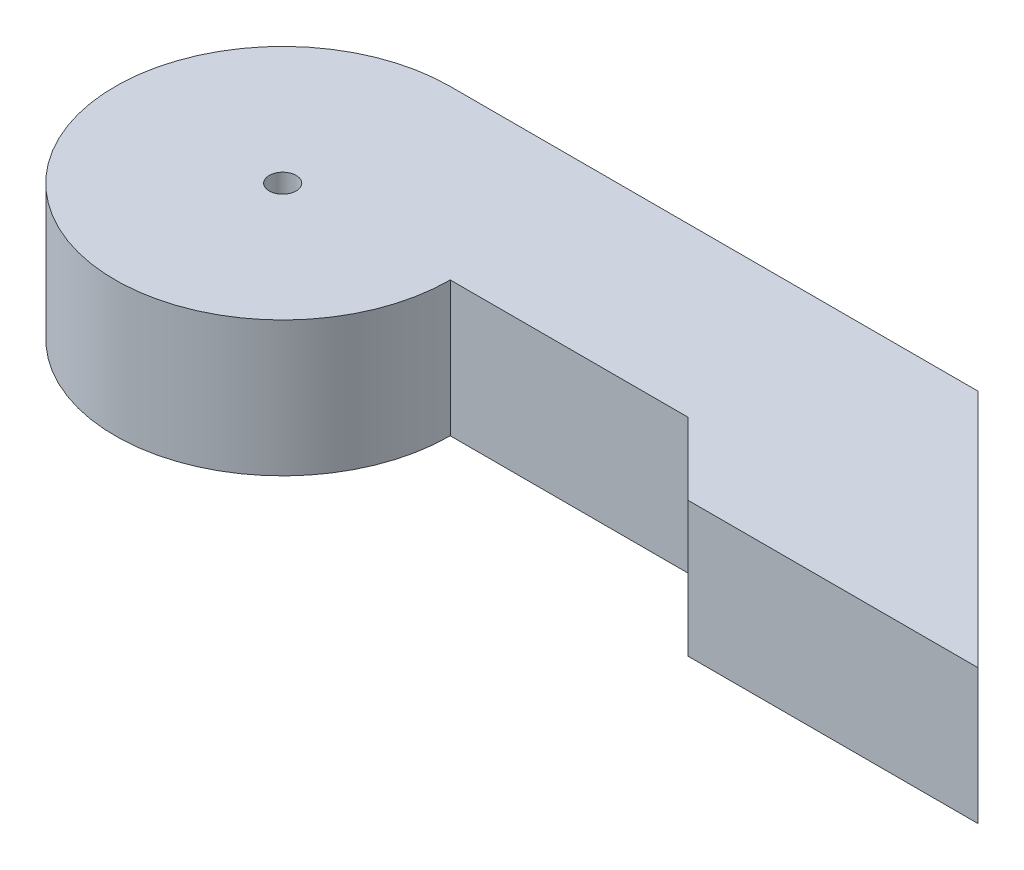
SolidWorks part; units mm, degrees
ref_plane "Front Plane" through (0, 0, 0) normal (0, 0, 1) x (1, 0, 0)
ref_plane "Top Plane" through (0, 0, 0) normal (0, 1, 0) x (1, 0, 0)
ref_plane "Right Plane" through (0, 0, 0) normal (1, 0, 0) x (0, 0, -1)
sketch "Sketch1" plane through (0, 0, 0) normal (0, 1, 0) x (1, 0, 0)
  line L0 (0, 12.4104) -> (0, 0)
  line L1 (0, 12.4104) -> (30.0174, 12.4104)
  line L2 (0, 0) -> (30.0174, 0)
  line L4 (30.0174, 0) -> (35.345, -5.3276)
  line L5 (35.345, -5.3276) -> (56.8244, -5.3276)
  line L6 (56.8244, -5.3276) -> (39.0865, 12.4104)
  line L7 (39.0865, 12.4104) -> (30.0174, 12.4104)
  line L8 (30.0174, 0) -> (30.0174, 12.4104)
  line L9 (30.0174, 12.4104) -> (39.0865, 12.4104)
  line L10 (30.0174, 0) -> (35.345, -5.3276)
  circle A0 centre (0, 0) radius 12.4104
  circle A1 centre (0, 0) radius 1
extrude "Boss-Extrude2" add sketch "Sketch1" along normal blind 10 contours A1 L2 A0 L0 | A1 L0 A0 L2 | A0 L2 L8 L1 | L8 L4 L5 L6 L7
